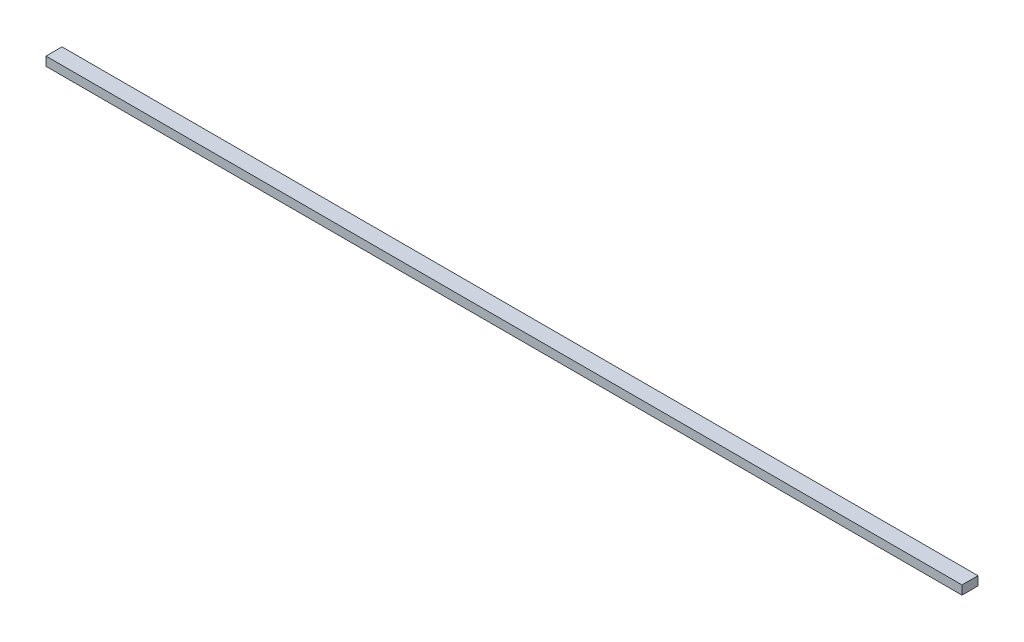
SolidWorks part; units mm, degrees
ref_plane "前视基准面" through (0, 0, 0) normal (0, 0, 1) x (1, 0, 0)
ref_plane "上视基准面" through (0, 0, 0) normal (0, 1, 0) x (1, 0, 0)
ref_plane "右视基准面" through (0, 0, 0) normal (1, 0, 0) x (0, 0, -1)
sketch "草图1" plane through (0, 0, 0) normal (0, 1, 0) x (1, 0, 0)
  line L1 (-257.5, -4.5) -> (257.5, -4.5)
  line L2 (-257.5, -4.5) -> (-257.5, 4.5)
  line L3 (-257.5, 4.5) -> (257.5, 4.5)
  line L4 (257.5, -4.5) -> (257.5, 4.5)
  line L5 (-257.5, -4.5) -> (257.5, 4.5) construction
  line L6 (-257.5, 4.5) -> (257.5, -4.5) construction
  point P0 (0, 0)
  dimension "D1" = 9
  dimension "D2" = 515
extrude "凸台-拉伸1" add sketch "草图1" along normal blind 5
